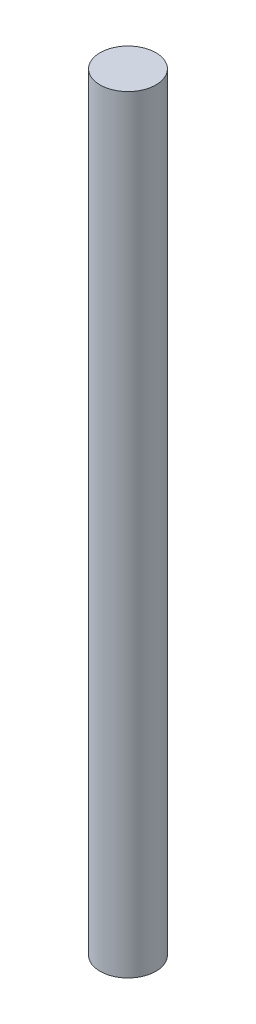
SolidWorks part; units mm, degrees
ref_plane "Front Plane" through (0, 0, 0) normal (0, 0, 1) x (1, 0, 0)
ref_plane "Top Plane" through (0, 0, 0) normal (0, 1, 0) x (1, 0, 0)
ref_plane "Right Plane" through (0, 0, 0) normal (1, 0, 0) x (0, 0, -1)
sketch "Sketch1" plane through (0, 0, 0) normal (0, 1, 0) x (1, 0, 0)
  circle A0 centre (0, 0) radius 0.8
  dimension "D1" = 1.6
extrude "Boss-Extrude1" add sketch "Sketch1" along normal blind 22
